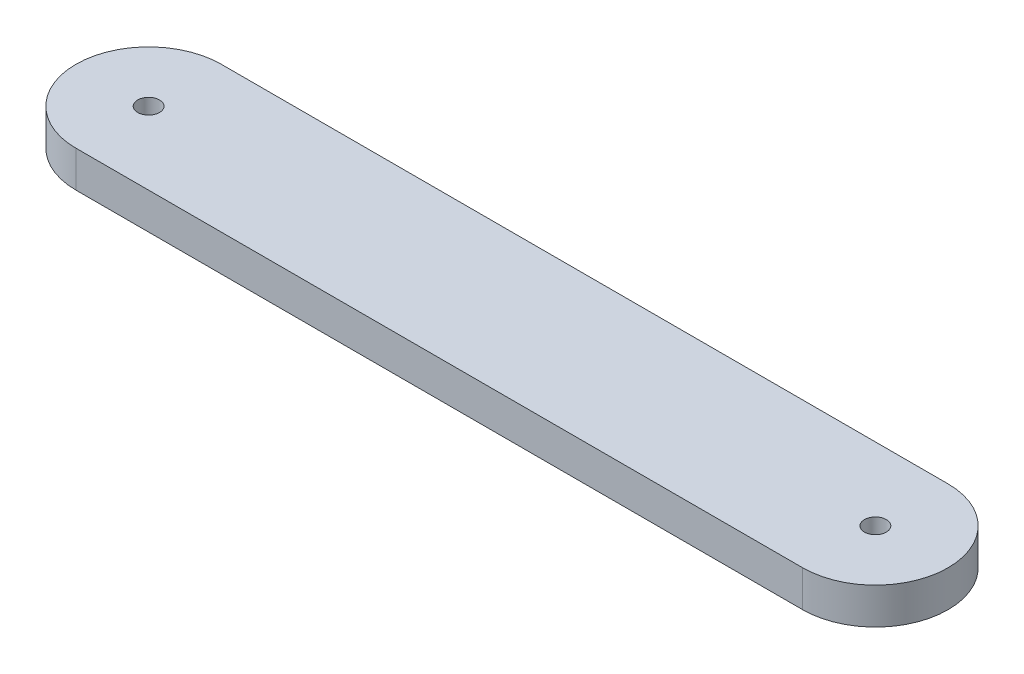
SolidWorks part; units mm, degrees
ref_plane "Front Plane" through (0, 0, 0) normal (0, 0, 1) x (1, 0, 0)
ref_plane "Top Plane" through (0, 0, 0) normal (0, 1, 0) x (1, 0, 0)
ref_plane "Right Plane" through (0, 0, 0) normal (1, 0, 0) x (0, 0, -1)
sketch "Sketch1" plane through (0, 0, 0) normal (0, 1, 0) x (1, 0, 0)
  line L0 (-50, 0) -> (50, 0) construction
  line L1 (-50, 10) -> (50, 10)
  line L2 (-50, -10) -> (50, -10)
  arc A0 (-50, 10) -> (-50, -10) centre (-50, 0) ccw
  arc A1 (50, -10) -> (50, 10) centre (50, 0) ccw
  point P3 (0, 0)
  dimension "D1" = 10
  dimension "D2" = 100
extrude "Boss-Extrude1" add sketch "Sketch1" along normal blind 5
sketch "Sketch2" plane through (0, 5, 0) normal (0, 1, 0) x (1, 0, 0)
  line L0 (0, -2.75) -> (0, 2.75) construction
  circle A0 centre (-50, 0) radius 1.5
  circle A1 centre (50, 0) radius 1.5
  dimension "D1" = 3
extrude "Cut-Extrude1" cut sketch "Sketch2" against normal up to next
equation "\"D1@Sketch1\" = \"Radius\""
equation "\"D2@Sketch1\" = \"Length\""
equation "\"D1@Boss-Extrude1\" = \"Thick\""
equation "\"Length\"= 100mm"
equation "\"Radius\"= 10mm"
equation "\"Thick\"= 5mm"
